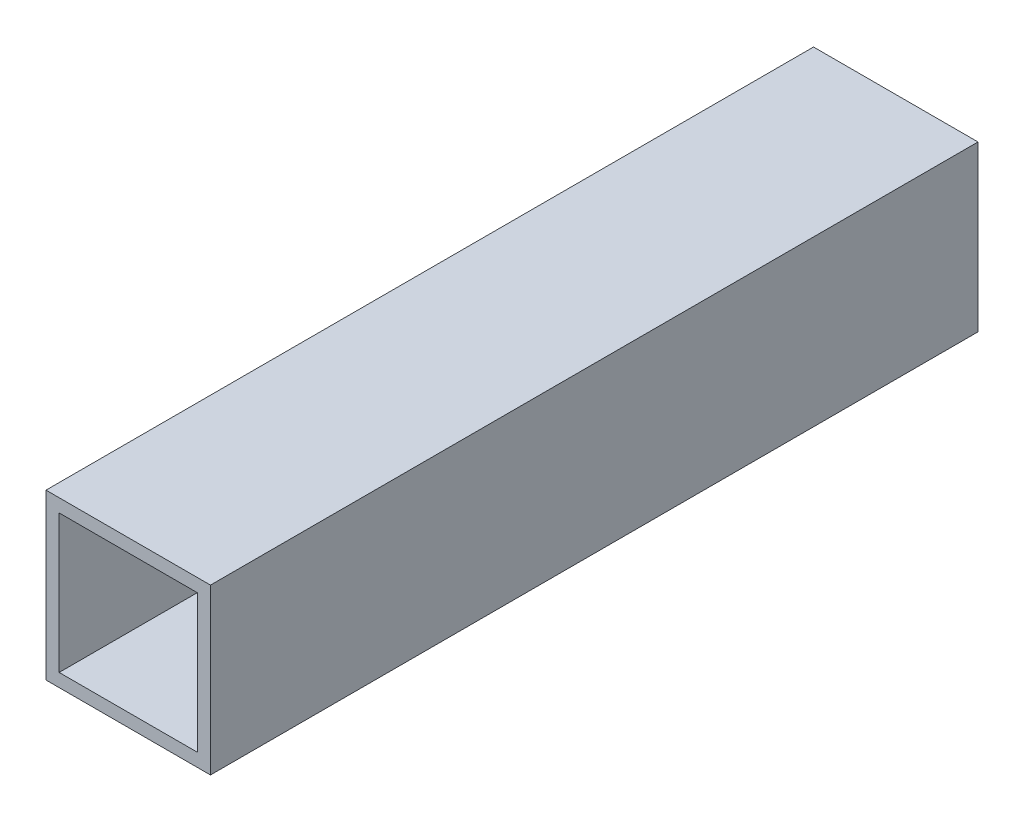
SolidWorks part; units mm, degrees
material "7050-T73510"
ref_plane "Front" through (0, 0, 0) normal (0, 0, 1) x (1, 0, 0)
ref_plane "Top" through (0, 0, 0) normal (0, 1, 0) x (1, 0, 0)
ref_plane "Right" through (0, 0, 0) normal (1, 0, 0) x (0, 0, -1)
sketch "草图1" plane through (0, 0, 0) normal (0, 0, 1) x (1, 0, 0)
  line L0 (-6.3, -6.3) -> (-6.3, 6.3)
  line L1 (-7.5, -7.5) -> (7.5, -7.5)
  line L2 (-7.5, -7.5) -> (-7.5, 7.5)
  line L3 (-7.5, 7.5) -> (7.5, 7.5)
  line L4 (7.5, -7.5) -> (7.5, 7.5)
  line L5 (-7.5, -7.5) -> (7.5, 7.5) construction
  line L6 (-7.5, 7.5) -> (7.5, -7.5) construction
  line L7 (-6.3, 6.3) -> (6.3, 6.3)
  line L8 (6.3, -6.3) -> (6.3, 6.3)
  line L9 (-6.3, -6.3) -> (6.3, -6.3)
  point P0 (0, 0)
  dimension "D1" = 15
  dimension "D2" = 15
  dimension "D3" = 1.2
extrude "凸台-拉伸1" add sketch "草图1" along normal blind 70
